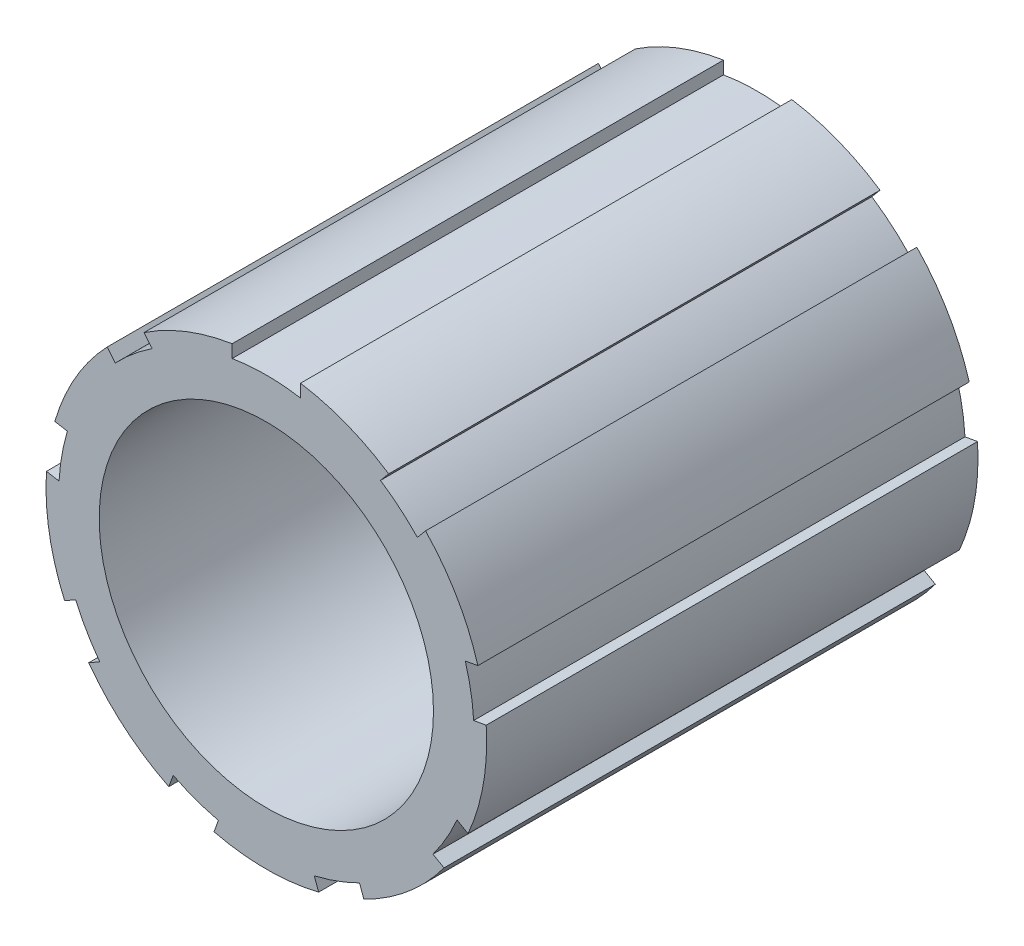
SolidWorks part; units mm, degrees
ref_plane "Alzado" through (0, 0, 0) normal (0, 0, 1) x (1, 0, 0)
ref_plane "Planta" through (0, 0, 0) normal (0, 1, 0) x (1, 0, 0)
ref_plane "Vista lateral" through (0, 0, 0) normal (1, 0, 0) x (0, 0, -1)
ref_plane "Plano_delante" through (0, 0, 2.5) normal (0, 0, 1) x (1, 0, 0)
sketch "Sk_Estriado" plane through (0, 0, 2.5) normal (0, 0, 1) x (1, 0, 0)
  line L0 (2.7, 17.1892) -> (2.7, 16.1762)
  line L1 (-2.7, 16.1762) -> (-2.7, 17.1892)
  line L2 (-9.6621, 14.4708) -> (-9.0152, 13.6998)
  line L3 (-11.9262, 11.2572) -> (-12.5731, 12.0282)
  line L4 (-16.7033, 4.8745) -> (-15.7122, 4.6998)
  line L5 (-16.372, 0.9575) -> (-17.3631, 1.1323)
  line L6 (-15.9287, -7.0025) -> (-15.0572, -6.4993)
  line L7 (-13.1572, -9.7902) -> (-14.0287, -10.2934)
  line L8 (-7.701, -15.603) -> (-7.3568, -14.6573)
  line L9 (-3.7859, -15.957) -> (-4.1301, -16.9027)
  line L10 (4.1301, -16.9027) -> (3.7859, -15.957)
  line L11 (7.3568, -14.6573) -> (7.701, -15.603)
  line L12 (14.0287, -10.2934) -> (13.1572, -9.7902)
  line L13 (15.0572, -6.4993) -> (15.9287, -7.0025)
  line L14 (17.3631, 1.1323) -> (16.372, 0.9575)
  line L15 (15.7122, 4.6998) -> (16.7033, 4.8745)
  line L16 (12.5731, 12.0282) -> (11.9262, 11.2572)
  line L17 (9.0152, 13.6998) -> (9.6621, 14.4708)
  arc A0 (2.7, 16.1762) -> (-2.7, 16.1762) centre (0, 0) ccw
  arc A1 (-2.7, 17.1892) -> (-9.6621, 14.4708) centre (0, 0) ccw
  arc A2 (-9.0152, 13.6998) -> (-11.9262, 11.2572) centre (0, 0) ccw
  arc A3 (-12.5731, 12.0282) -> (-16.7033, 4.8745) centre (0, 0) ccw
  arc A4 (-15.7122, 4.6998) -> (-16.372, 0.9575) centre (0, 0) ccw
  arc A5 (-17.3631, 1.1323) -> (-15.9287, -7.0025) centre (0, 0) ccw
  arc A6 (-15.0572, -6.4993) -> (-13.1572, -9.7902) centre (0, 0) ccw
  arc A7 (-14.0287, -10.2934) -> (-7.701, -15.603) centre (0, 0) ccw
  arc A8 (-7.3568, -14.6573) -> (-3.7859, -15.957) centre (0, 0) ccw
  arc A9 (-4.1301, -16.9027) -> (4.1301, -16.9027) centre (0, 0) ccw
  arc A10 (3.7859, -15.957) -> (7.3568, -14.6573) centre (0, 0) ccw
  arc A11 (7.701, -15.603) -> (14.0287, -10.2934) centre (0, 0) ccw
  arc A12 (13.1572, -9.7902) -> (15.0572, -6.4993) centre (0, 0) ccw
  arc A13 (15.9287, -7.0025) -> (17.3631, 1.1323) centre (0, 0) ccw
  arc A14 (16.372, 0.9575) -> (15.7122, 4.6998) centre (0, 0) ccw
  arc A15 (16.7033, 4.8745) -> (12.5731, 12.0282) centre (0, 0) ccw
  arc A16 (11.9262, 11.2572) -> (9.0152, 13.6998) centre (0, 0) ccw
  arc A17 (9.6621, 14.4708) -> (2.7, 17.1892) centre (0, 0) ccw
  circle A18 centre (0, 0) radius 13.2
  dimension "D1" = 34.8
  dimension "D2" = 32.8
  dimension "D3" = 26.4
  dimension "D4" = 5.4
  dimension "D5" = 3.8
extrude "Eje" add sketch "Sk_Estriado" against normal blind 38.8
